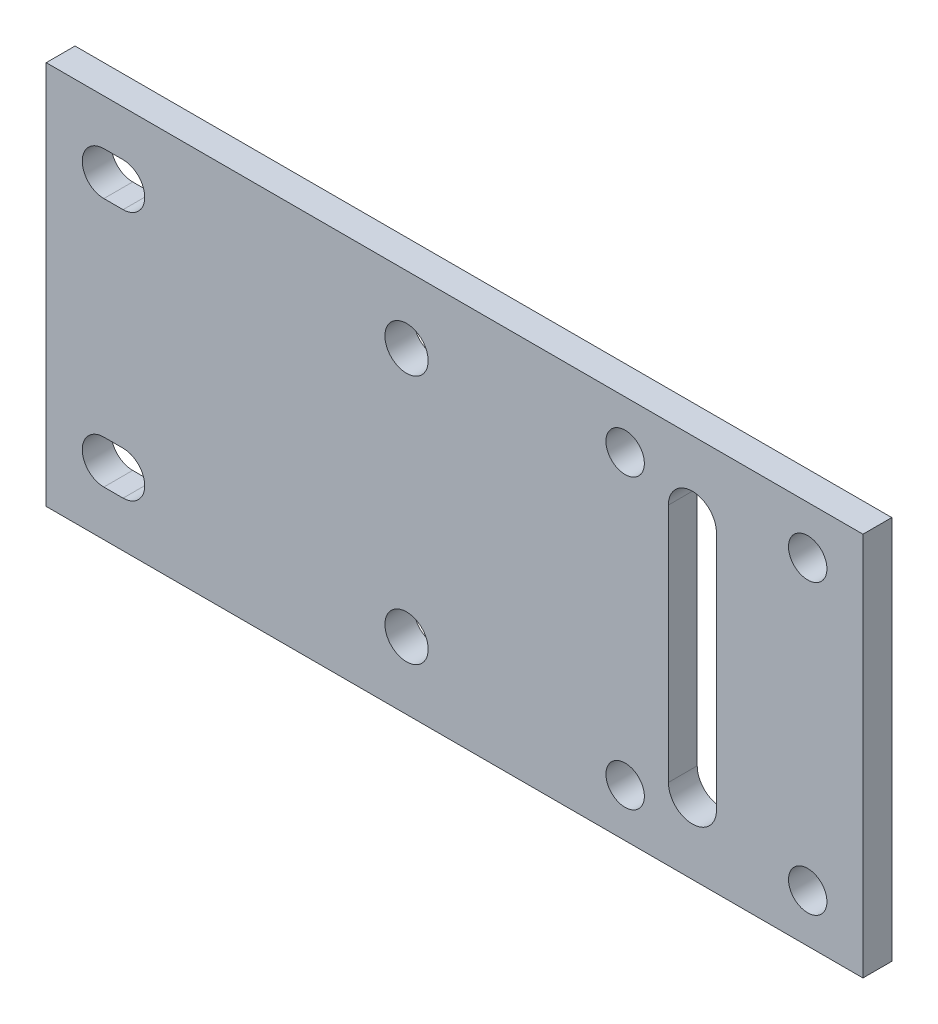
SolidWorks part; units mm, degrees
material "6061 合金"
ref_plane "前视基准面" through (0, 0, 0) normal (0, 0, 1) x (1, 0, 0)
ref_plane "上视基准面" through (0, 0, 0) normal (0, 1, 0) x (1, 0, 0)
ref_plane "右视基准面" through (0, 0, 0) normal (1, 0, 0) x (0, 0, -1)
sketch "草图1" plane through (0, 0, 0) normal (0, 0, 1) x (1, 0, 0)
  line L0 (-14.25, 13) -> (-16.25, 13) construction
  line L1 (-15.25, -13) -> (15.25, -13) construction
  line L2 (-15.25, -13) -> (-15.25, 13) construction
  line L3 (-15.25, 13) -> (15.25, 13) construction
  line L4 (15.25, -13) -> (15.25, 13) construction
  line L5 (-15.25, -13) -> (15.25, 13) construction
  line L6 (-15.25, 13) -> (15.25, -13) construction
  line L7 (-14.25, 10.75) -> (-16.25, 10.75)
  line L8 (-14.25, 15.25) -> (-16.25, 15.25)
  line L9 (-14.25, -13) -> (-16.25, -13) construction
  line L10 (-14.25, -15.25) -> (-16.25, -15.25)
  line L11 (-14.25, -10.75) -> (-16.25, -10.75)
  line L12 (45, 0) -> (45, 16.5575) construction
  line L13 (62.75, -20) -> (-22.25, -20)
  line L14 (62.75, -20) -> (62.75, 20)
  line L15 (62.75, 20) -> (-22.25, 20)
  line L16 (-22.25, -20) -> (-22.25, 20)
  line L17 (62.75, -20) -> (-22.25, 20) construction
  line L18 (62.75, 20) -> (-22.25, -20) construction
  line L19 (45, -12.5) -> (45, 12.5) construction
  line L20 (42.5, -12.5) -> (42.5, 12.5)
  line L21 (47.5, -12.5) -> (47.5, 12.5)
  line L22 (55, 0) -> (-55, 0) construction
  circle A0 centre (15.25, 13) radius 2.25
  circle A1 centre (15.25, -13) radius 2.25
  arc A2 (-14.25, 10.75) -> (-14.25, 15.25) centre (-14.25, 13) ccw
  arc A3 (-16.25, 15.25) -> (-16.25, 10.75) centre (-16.25, 13) ccw
  arc A4 (-14.25, -15.25) -> (-14.25, -10.75) centre (-14.25, -13) ccw
  arc A5 (-16.25, -10.75) -> (-16.25, -15.25) centre (-16.25, -13) ccw
  arc A6 (42.5, -12.5) -> (47.5, -12.5) centre (45, -12.5) ccw
  arc A7 (47.5, 12.5) -> (42.5, 12.5) centre (45, 12.5) ccw
  circle A8 centre (57, 15) radius 2
  circle A9 centre (38, 15) radius 2
  circle A11 centre (57, -15) radius 2
  circle A12 centre (38, -15) radius 2
  point P0 (0, 0)
  point P10 (-15.25, 13)
  point P17 (-15.25, -13)
  point P22 (-15.25, 10.75)
  point P23 (-15.25, -10.75)
  point P24 (17, 0)
  point P33 (45, 0)
  point P48 (20.25, 0)
  dimension "D3" = 4.5
  dimension "D4" = 4.5
  dimension "D6" = 85
  dimension "D15" = 2.5
  dimension "D12" = 4
  dimension "D16" = 4
  dimension "D1" = 30.5
  dimension "D2" = 26
  dimension "D5" = 4.5
  dimension "D7" = 2
  dimension "D8" = 4.5
  dimension "D9" = 2
  dimension "D10" = 40
  dimension "D11" = 17
  dimension "D13" = 45
  dimension "D14" = 25
  dimension "D17" = 12
  dimension "D18" = 7
  dimension "D19" = 15
  dimension "D20" = 7
extrude "凸台-拉伸1" add sketch "草图1" along normal blind 3
